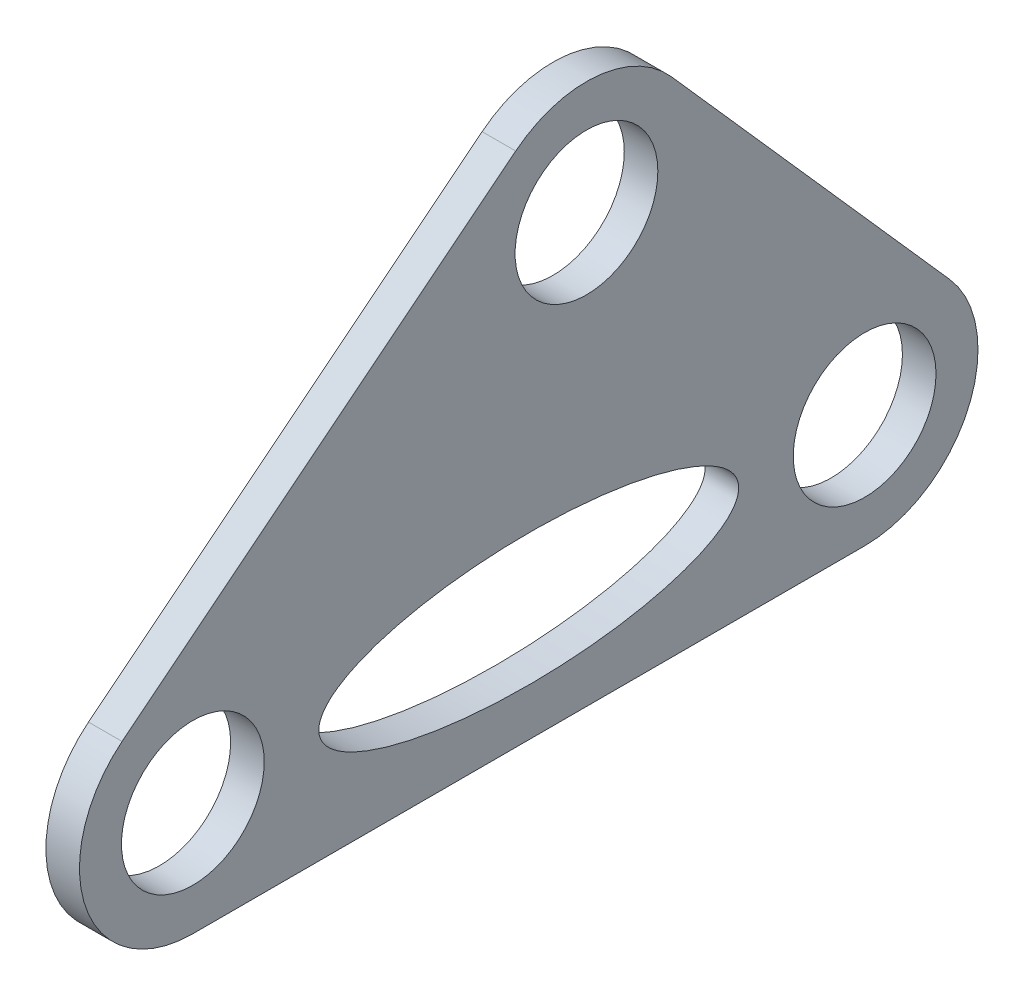
SolidWorks part; units mm, degrees
ref_plane "前视基准面" through (0, 0, 0) normal (0, 0, 1) x (1, 0, 0)
ref_plane "上视基准面" through (0, 0, 0) normal (0, 1, 0) x (1, 0, 0)
ref_plane "右视基准面" through (0, 0, 0) normal (1, 0, 0) x (0, 0, -1)
sketch "草图2" plane through (0, 0, 0) normal (1, 0, 0) x (0, 0, -1)
  line L0 (0, 0) -> (80, 0) construction
  line L1 (46.875, 37.4531) -> (80, 0) construction
  line L2 (46.875, 37.4531) -> (0, 0) construction
  line L3 (-8.4269, 10.5469) -> (38.4481, 48)
  line L4 (56.9873, 46.3968) -> (90.1123, 8.9437)
  line L5 (80, -13.5) -> (0, -13.5)
  circle A0 centre (0, 0) radius 8.5
  circle A1 centre (46.875, 37.4531) radius 8.5
  circle A2 centre (80, 0) radius 8.5
  circle A3 centre (0, 0) radius 13.5 construction
  circle A4 centre (46.875, 37.4531) radius 13.5 construction
  circle A5 centre (80, 0) radius 13.5 construction
  arc A6 (-8.4269, 10.5469) -> (0, -13.5) centre (0, 0) ccw
  arc A7 (80, -13.5) -> (90.1123, 8.9437) centre (80, 0) ccw
  arc A8 (38.4481, 48) -> (56.9873, 46.3968) centre (46.875, 37.4531) cw
  dimension "D2" = 5
  dimension "D1" = 80
extrude "凸台-拉伸1" add sketch "草图2" along normal blind 4 contours A8 L3 A6 L5 A7 L4 A2 A1 A0
sketch "草图3" plane through (4, 0, 0) normal (1, 0, 0) x (0, 0, -1)
  line L0 (0, 0) -> (80, 0) construction
  ellipse E0 centre (40, 0) end of major axis (65, 0) minor radius 7.8487
extrude "切除-拉伸1" cut sketch "草图3" against normal blind 10
